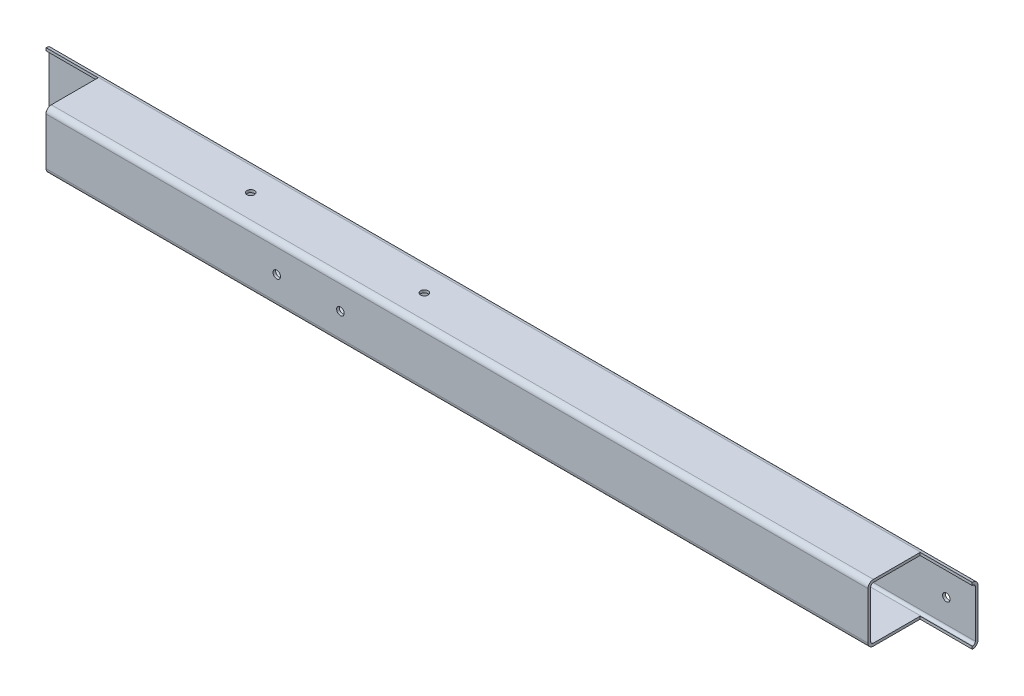
SolidWorks part; units mm, degrees
ref_plane "Front Plane" through (0, 0, 0) normal (0, 0, 1) x (1, 0, 0)
ref_plane "Top Plane" through (0, 0, 0) normal (0, 1, 0) x (1, 0, 0)
ref_plane "Right Plane" through (0, 0, 0) normal (1, 0, 0) x (0, 0, -1)
sketch "Sketch1" plane through (0, 0, 0) normal (0, 0, 1) x (1, 0, 0)
  line L0 (-400, 0) -> (400, 0)
  point P4 (0, 0)
  dimension "D1" = 800
other "Shs c450 as 50X50X2.3 SHS C450(1)"
ref_plane "Plane1" through (-400, 0, 0) normal (1, 0, 0) x (0, 1, 0)
sketch "Sketch19" plane through (-400, 0, 0) normal (1, 0, 0) x (0, 1, 0)
  line L0 (-20.4, 22.7) -> (20.4, 22.7)
  line L1 (-20.4, -25) -> (20.4, -25)
  line L2 (-25, -20.4) -> (-25, 20.4)
  line L3 (-20.4, 25) -> (20.4, 25)
  line L4 (25, -20.4) -> (25, 20.4)
  line L5 (-25, -25) -> (25, 25) construction
  line L6 (-25, 25) -> (25, -25) construction
  line L7 (22.7, -20.4) -> (22.7, 20.4)
  line L8 (-20.4, -22.7) -> (20.4, -22.7)
  line L9 (-22.7, -20.4) -> (-22.7, 20.4)
  arc A0 (-25, 20.4) -> (-20.4, 25) centre (-20.4, 20.4) cw
  arc A1 (20.4, 25) -> (25, 20.4) centre (20.4, 20.4) cw
  arc A2 (-20.4, -25) -> (-25, -20.4) centre (-20.4, -20.4) cw
  arc A3 (20.4, -25) -> (25, -20.4) centre (20.4, -20.4) ccw
  arc A4 (-22.7, 20.4) -> (-20.4, 22.7) centre (-20.4, 20.4) cw
  arc A5 (20.4, 22.7) -> (22.7, 20.4) centre (20.4, 20.4) cw
  arc A6 (20.4, -22.7) -> (22.7, -20.4) centre (20.4, -20.4) ccw
  arc A7 (-20.4, -22.7) -> (-22.7, -20.4) centre (-20.4, -20.4) cw
  point P0 (0, 0)
  point P30 (-25, 0)
  point P31 (0, 25)
  point P32 (25, 0)
  point P33 (0, -25)
  point P34 (0, 0)
  dimension "D2" = 4.6
  dimension "Thickness" = 2.3
  dimension "Width" = 50
sketch "Sketch20" plane through (0, 0, 0) normal (0, 1, 0) x (1, 0, 0)
  line L9 (-400, -25) -> (-355, -25)
  line L10 (-400, -25) -> (-400, 20)
  line L11 (-400, 20) -> (-355, 20)
  line L12 (-355, -25) -> (-355, 20)
  line L13 (400, -25) -> (355, -25)
  line L14 (400, -25) -> (400, 20)
  line L15 (400, 20) -> (355, 20)
  line L16 (355, -25) -> (355, 20)
  dimension "D1" = 45
extrude "Cut-Extrude1" cut sketch "Sketch20" against normal through all both and the other way through all
sketch "Sketch21" plane through (0, 0, -25) normal (0, 0, -1) x (-1, 0, 0)
  line L0 (-375, 0) -> (375, 0) construction
  circle A0 centre (-375, 0) radius 3.25
  circle A1 centre (375, 0) radius 3.25
  point P4 (0, 0)
  dimension "D2" = 6.5
  dimension "D1" = 750
extrude "Cut-Extrude2" cut sketch "Sketch21" against normal blind 10
sketch "Sketch22" plane through (0, 0, 25) normal (0, 0, 1) x (1, 0, 0)
  line L0 (-155.7, 0) -> (-100.7, 0) construction
  line L2 (400, -20.4) -> (400, 20.4) construction
  circle A0 centre (-155.7, 0) radius 3.25
  circle A1 centre (-100.7, 0) radius 3.25
  point P4 (-128.2, 0)
  dimension "D3" = 6.5
  dimension "D1" = 55
  dimension "D2" = 500.7
extrude "Cut-Extrude3" cut sketch "Sketch22" against normal through all
sketch "Sketch23" plane through (0, 25, 0) normal (0, 1, 0) x (1, 0, 0)
  line L0 (-203.2, 0) -> (-53.2, 0) construction
  line L1 (-152.45, -23.85) -> (-103.95, -23.85) construction
  line L2 (-152.45, -25) -> (-152.45, -22.7) construction
  line L3 (-103.95, -22.7) -> (-103.95, -25) construction
  line L4 (-128.2, -23.85) -> (-128.2, 0) construction
  circle A0 centre (-203.2, 0) radius 3.25
  circle A1 centre (-53.2, 0) radius 3.25
  point P4 (-128.2, 0)
  dimension "D2" = 6.5
  dimension "D1" = 150
extrude "Cut-Extrude4" cut sketch "Sketch23" against normal through all
